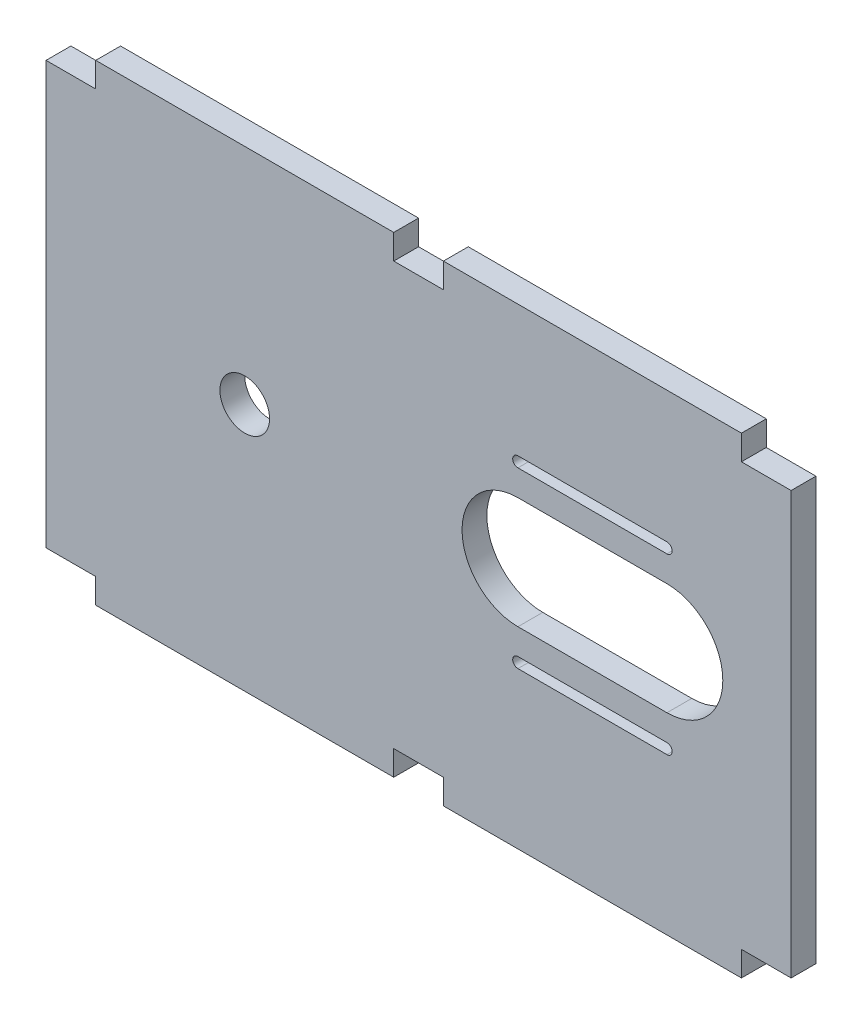
SolidWorks part; units mm, degrees
ref_plane "Ön Düzlem" through (0, 0, 0) normal (0, 0, 1) x (1, 0, 0)
ref_plane "Üst Düzlem" through (0, 0, 0) normal (0, 1, 0) x (1, 0, 0)
ref_plane "Sağ Düzlem" through (0, 0, 0) normal (1, 0, 0) x (0, 0, -1)
sketch "Çizim1" plane through (0, 0, 0) normal (0, 0, 1) x (1, 0, 0)
  line L0 (100, 10) -> (40, 10) construction
  line L1 (-150, -90) -> (150, -90)
  line L2 (-150, -90) -> (-150, 90)
  line L3 (-150, 90) -> (150, 90)
  line L4 (150, -90) -> (150, 90)
  line L5 (-150, -90) -> (150, 90) construction
  line L6 (-150, 90) -> (150, -90) construction
  line L7 (100, -12.5) -> (40, -12.5)
  line L8 (100, 32.5) -> (40, 32.5)
  line L9 (100, 45) -> (40, 45) construction
  line L10 (100, 42.9) -> (40, 42.9)
  line L11 (100, 47.1) -> (40, 47.1)
  line L12 (100, -25) -> (40, -25) construction
  line L13 (100, -27.1) -> (40, -27.1)
  line L14 (100, -22.9) -> (40, -22.9)
  arc A0 (100, 42.9) -> (100, 47.1) centre (100, 45) ccw
  circle A1 centre (-70, 10) radius 10
  arc A2 (100, -12.5) -> (100, 32.5) centre (100, 10) ccw
  arc A3 (40, 32.5) -> (40, -12.5) centre (40, 10) ccw
  arc A4 (40, 47.1) -> (40, 42.9) centre (40, 45) ccw
  arc A5 (100, -27.1) -> (100, -22.9) centre (100, -25) ccw
  arc A6 (40, -22.9) -> (40, -27.1) centre (40, -25) ccw
  point P0 (0, 0)
  point P8 (70, 10)
  point P17 (70, 45)
  point P22 (70, -25)
  dimension "D3" = 100
  dimension "D5" = 35
  dimension "D1" = 80
  dimension "D2" = 180
  dimension "D4" = 100
  dimension "D6" = 35
  dimension "D7" = 4.2
  dimension "D8" = 300
  dimension "D9" = 60
  dimension "D10" = 80
  dimension "D11" = 60
  dimension "D12" = 60
  dimension "D13" = 45
extrude "Yükseklik-Ekstrüzyon1" add sketch "Çizim1" along normal blind 10
sketch "Çizim3" plane through (0, 90, 0) normal (0, 1, 0) x (1, 0, 0)
  line L0 (130, 0) -> (130, -10)
  line L1 (130, 0) -> (10, 0)
  line L2 (130, -10) -> (10, -10)
  line L3 (10, 0) -> (10, -10)
  line L4 (150, 0) -> (-150, 0) construction
  line L5 (150, -10) -> (-150, -10) construction
  line L6 (-10, 0) -> (-10, -10)
  line L7 (-10, 0) -> (-130, 0)
  line L8 (-10, -10) -> (-130, -10)
  line L9 (-130, 0) -> (-130, -10)
  line L10 (150, -10) -> (150, 0) construction
  line L11 (-150, -10) -> (-150, 0) construction
  point P16 (0, 0)
  dimension "D1" = 20
  dimension "D2" = 20
  dimension "D3" = 20
  dimension "D4" = 10
extrude "Yükseklik-Ekstrüzyon2" add sketch "Çizim3" along normal blind 10
sketch "Çizim4" plane through (0, -90, 0) normal (0, -1, 0) x (1, 0, 0)
  line L0 (150, 0) -> (150, 10)
  line L1 (150, 0) -> (130, 0)
  line L2 (150, 10) -> (130, 10)
  line L3 (130, 0) -> (130, 10)
  line L4 (10, 10) -> (10, 0)
  line L5 (10, 10) -> (-10, 10)
  line L6 (10, 0) -> (-10, 0)
  line L7 (-10, 10) -> (-10, 0)
  line L8 (-150, 0) -> (150, 0) construction
  line L9 (-150, 10) -> (150, 10) construction
  line L10 (-150, 0) -> (-150, 10)
  line L11 (-150, 0) -> (-130, 0)
  line L12 (-150, 10) -> (-130, 10)
  line L13 (-130, 0) -> (-130, 10)
  dimension "D1" = 20
  dimension "D2" = 120
  dimension "D3" = 20
  dimension "D4" = 20
extrude "Kes-Ekstrüzyon1" cut sketch "Çizim4" against normal blind 10
sketch "Çizim6" plane through (0, 0, 0) normal (0, 0, -1) x (-1, 0, 0)
  line L0 (-141.6, 78.8) -> (-141.6, 90)
  line L1 (-141.6, 78.8) -> (-138.4, 78.8)
  line L2 (-141.6, 90) -> (-138.4, 90)
  line L3 (-138.4, 78.8) -> (-138.4, 90)
  line L4 (-141.6, 78.8) -> (-138.4, 90) construction
  line L5 (-141.6, 90) -> (-138.4, 78.8) construction
  line L6 (-150, -80) -> (-150, 90) construction
  line L7 (-150, 90) -> (-130, 90) construction
  line L8 (-142.8, 85) -> (-137.2, 85)
  line L9 (-142.8, 85) -> (-142.8, 82.3)
  line L10 (-137.2, 85) -> (-137.2, 82.3)
  line L11 (-142.8, 82.3) -> (-137.2, 82.3)
  line L12 (-142.8, 85) -> (-137.2, 82.3) construction
  line L13 (-137.2, 85) -> (-142.8, 82.3) construction
  line L14 (-1.6, 78.8) -> (-1.6, 90)
  line L15 (-1.6, 78.8) -> (1.6, 78.8)
  line L16 (-1.6, 90) -> (1.6, 90)
  line L17 (1.6, 78.8) -> (1.6, 90)
  line L18 (-2.8, 85) -> (2.8, 85)
  line L19 (-2.8, 85) -> (-2.8, 82.3)
  line L20 (2.8, 85) -> (2.8, 82.3)
  line L21 (-2.8, 82.3) -> (2.8, 82.3)
  line L22 (-1.6, 78.8) -> (1.6, 90) construction
  line L23 (-1.6, 90) -> (1.6, 78.8) construction
  line L24 (-2.8, 85) -> (2.8, 82.3) construction
  line L25 (2.8, 85) -> (-2.8, 82.3) construction
  line L26 (138.4, 78.8) -> (138.4, 90)
  line L27 (138.4, 78.8) -> (141.6, 78.8)
  line L28 (138.4, 90) -> (141.6, 90)
  line L29 (141.6, 78.8) -> (141.6, 90)
  line L30 (137.2, 85) -> (142.8, 85)
  line L31 (137.2, 85) -> (137.2, 82.3)
  line L32 (142.8, 85) -> (142.8, 82.3)
  line L33 (137.2, 82.3) -> (142.8, 82.3)
  line L34 (138.4, 78.8) -> (141.6, 90) construction
  line L35 (138.4, 90) -> (141.6, 78.8) construction
  line L36 (137.2, 85) -> (142.8, 82.3) construction
  line L37 (142.8, 85) -> (137.2, 82.3) construction
  line L42 (142.8, -75) -> (137.2, -72.3) construction
  line L43 (137.2, -75) -> (142.8, -72.3) construction
  line L44 (138.4, -80) -> (141.6, -68.8) construction
  line L45 (138.4, -68.8) -> (141.6, -80) construction
  line L46 (2.8, -75) -> (-2.8, -72.3) construction
  line L47 (-2.8, -75) -> (2.8, -72.3) construction
  line L48 (-1.6, -80) -> (1.6, -68.8) construction
  line L49 (-1.6, -68.8) -> (1.6, -80) construction
  line L50 (-137.2, -75) -> (-142.8, -72.3) construction
  line L51 (-142.8, -75) -> (-137.2, -72.3) construction
  line L52 (-141.6, -80) -> (-138.4, -68.8) construction
  line L53 (-141.6, -68.8) -> (-138.4, -80) construction
  line L54 (137.2, -72.3) -> (142.8, -72.3)
  line L55 (142.8, -75) -> (142.8, -72.3)
  line L56 (137.2, -75) -> (137.2, -72.3)
  line L57 (137.2, -75) -> (142.8, -75)
  line L58 (141.6, -68.8) -> (141.6, -80)
  line L59 (138.4, -80) -> (141.6, -80)
  line L60 (138.4, -68.8) -> (141.6, -68.8)
  line L61 (138.4, -68.8) -> (138.4, -80)
  line L62 (-2.8, -72.3) -> (2.8, -72.3)
  line L63 (2.8, -75) -> (2.8, -72.3)
  line L64 (-2.8, -75) -> (-2.8, -72.3)
  line L65 (-2.8, -75) -> (2.8, -75)
  line L66 (1.6, -68.8) -> (1.6, -80)
  line L67 (-1.6, -80) -> (1.6, -80)
  line L68 (-1.6, -68.8) -> (1.6, -68.8)
  line L69 (-1.6, -68.8) -> (-1.6, -80)
  line L70 (-142.8, -72.3) -> (-137.2, -72.3)
  line L71 (-137.2, -75) -> (-137.2, -72.3)
  line L72 (-142.8, -75) -> (-142.8, -72.3)
  line L73 (-142.8, -75) -> (-137.2, -75)
  line L74 (-138.4, -68.8) -> (-138.4, -80)
  line L75 (-141.6, -80) -> (-138.4, -80)
  line L76 (-141.6, -68.8) -> (-138.4, -68.8)
  line L77 (-141.6, -68.8) -> (-141.6, -80)
  point P1 (-140, 84.4)
  point P10 (-140, 83.65)
  point P12 (0, 84.4)
  point P21 (0, 83.65)
  point P26 (140, 84.4)
  point P31 (140, 83.65)
  point P67 (140, -73.65)
  point P68 (140, -74.4)
  point P69 (0, -74.4)
  point P70 (-140, -74.4)
  dimension "D1" = 8.4
  dimension "D2" = 3.2
  dimension "D3" = 11.2
  dimension "D4" = 5
  dimension "D5" = 3
